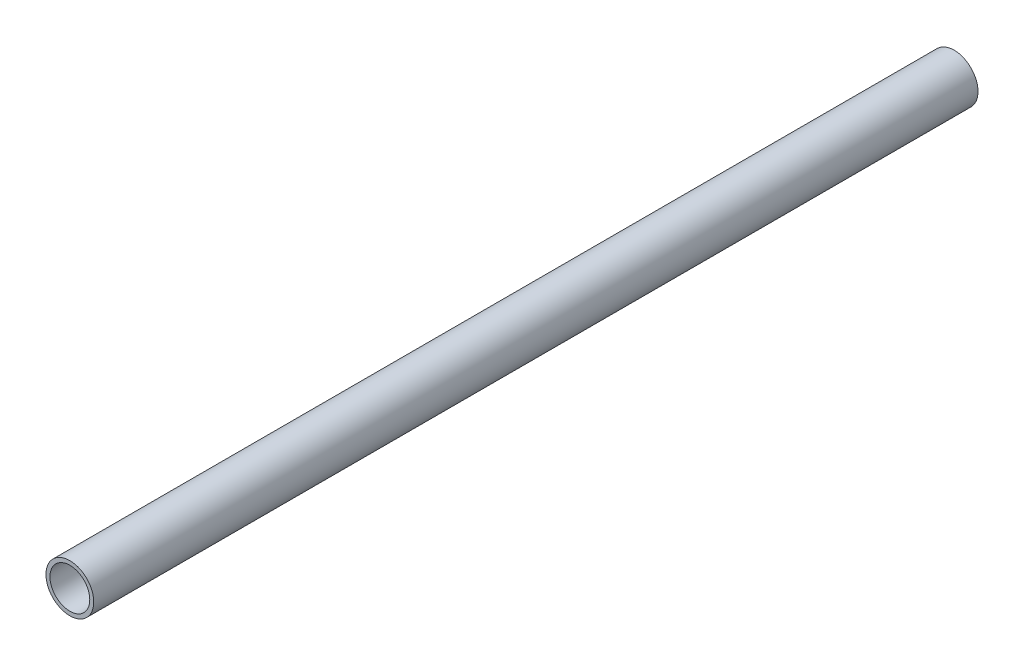
SolidWorks part; units mm, degrees
material "Thornel Mat VMA"
ref_plane "Front Plane" through (0, 0, 0) normal (0, 0, 1) x (1, 0, 0)
ref_plane "Top Plane" through (0, 0, 0) normal (0, 1, 0) x (1, 0, 0)
ref_plane "Right Plane" through (0, 0, 0) normal (1, 0, 0) x (0, 0, -1)
sketch "Sketch1" plane through (0, 0, 0) normal (0, 0, 1) x (1, 0, 0)
  circle A0 centre (0, 0) radius 9
  circle A1 centre (0, 0) radius 7.5
  dimension "D1" = 18
  dimension "D2" = 15
extrude "Boss-Extrude1" add sketch "Sketch1" along normal blind 333
